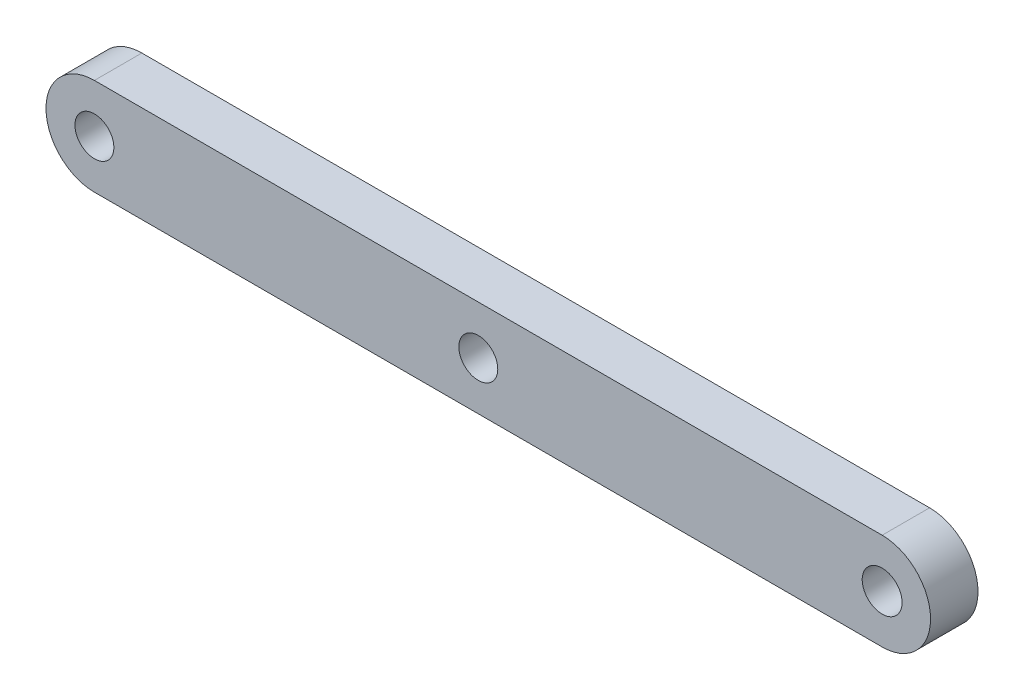
SolidWorks part; units mm, degrees
ref_plane "Plan de face" through (0, 0, 0) normal (0, 0, 1) x (1, 0, 0)
ref_plane "Plan de dessus" through (0, 0, 0) normal (0, 1, 0) x (1, 0, 0)
ref_plane "Plan de droite" through (0, 0, 0) normal (1, 0, 0) x (0, 0, -1)
sketch "Esquisse1" plane through (0, 0, 0) normal (0, 0, 1) x (1, 0, 0)
  line L0 (0, 0) -> (-83, 0) construction
  line L1 (0, -5.1) -> (-83, -5.1)
  line L2 (0, 5.1) -> (-83, 5.1)
  circle A0 centre (0, 0) radius 2.1
  circle A1 centre (-42.55, 0) radius 2.05
  circle A2 centre (-83, 0) radius 2.05
  arc A3 (0, -5.1) -> (0, 5.1) centre (0, 0) ccw
  arc A4 (-83, 5.1) -> (-83, -5.1) centre (-83, 0) ccw
  point P7 (-41.5, 0)
  point P12 (0, 2.1)
  dimension "D1" = 4.1
  dimension "D2" = 4.2
  dimension "D3" = 3
  dimension "D4" = 42.55
  dimension "D5" = 40.45
extrude "Boss.-Extru.1" add sketch "Esquisse1" along normal blind 5
